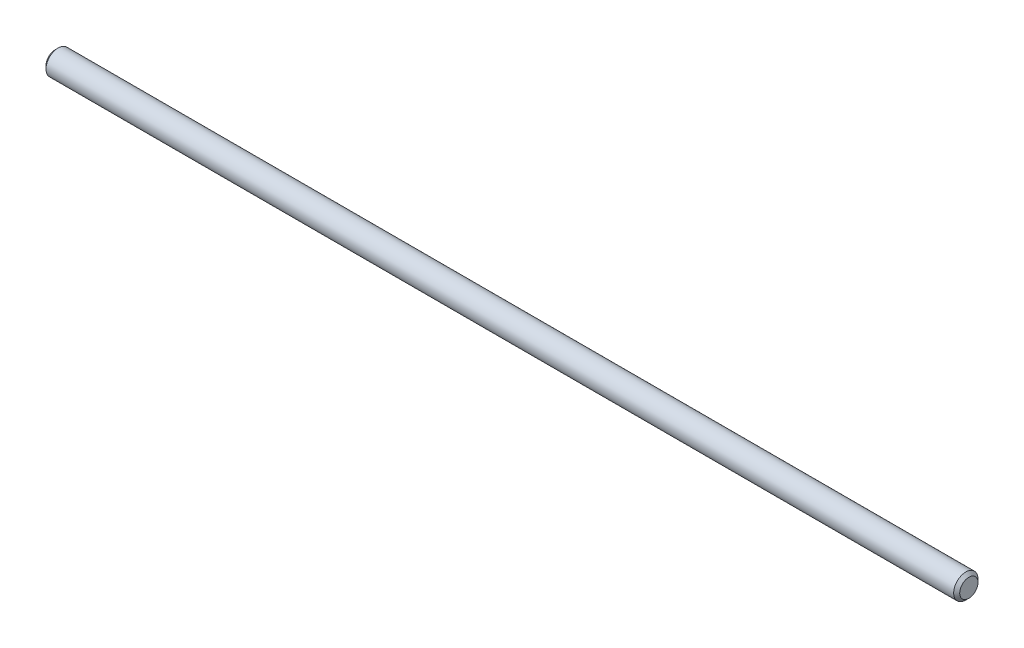
SolidWorks part; units mm, degrees
ref_plane "Alzado" through (0, 0, 0) normal (0, 0, 1) x (1, 0, 0)
ref_plane "Planta" through (0, 0, 0) normal (0, 1, 0) x (1, 0, 0)
ref_plane "Vista lateral" through (0, 0, 0) normal (1, 0, 0) x (0, 0, -1)
sketch "Croquis1" plane through (0, 0, 0) normal (1, 0, 0) x (0, 0, -1)
  circle A0 centre (0, 0) radius 4
  dimension "D1" = 8
extrude "Saliente-Extruir1" add sketch "Croquis1" along normal blind 300
cosmetic thread "Rosca cosmética3" parameters "D1"=198.9999, "D2"=6.891
cosmetic thread "Rosca cosmética4" parameters "D2"=6.891
chamfer "Chaflán1" distance 1 angle 45 1 edges at (300, 0, -4)
chamfer "Chaflán2" distance 1 angle 45 1 edges at (0, 0, -4)
